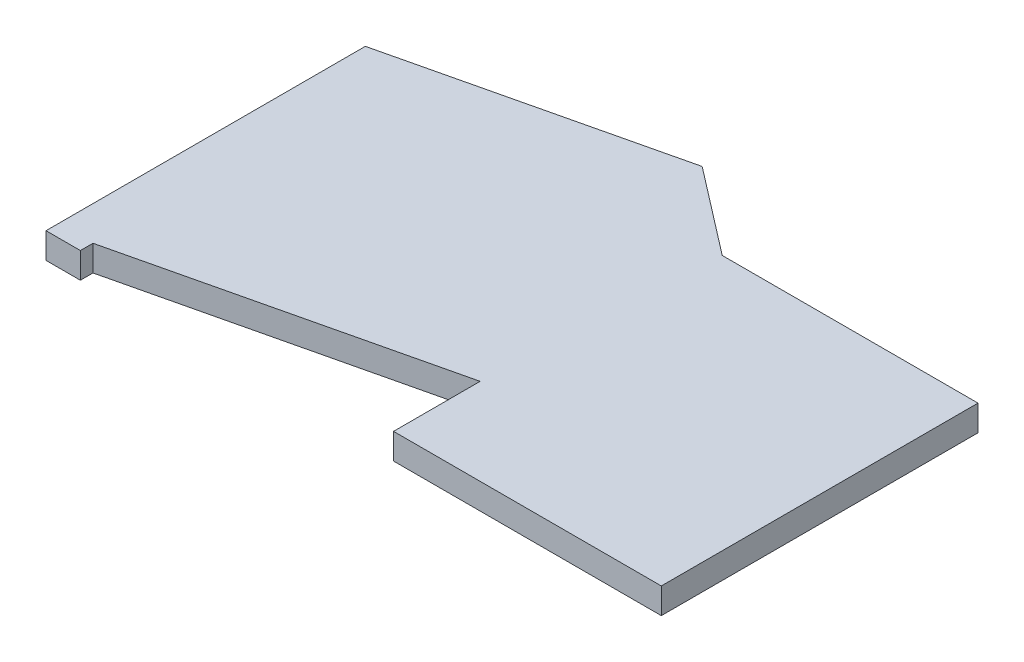
SolidWorks part; units mm, degrees
ref_plane "Front Plane" through (0, 0, 0) normal (0, 0, 1) x (1, 0, 0)
ref_plane "Top Plane" through (0, 0, 0) normal (0, 1, 0) x (1, 0, 0)
ref_plane "Right Plane" through (0, 0, 0) normal (1, 0, 0) x (0, 0, -1)
sketch "Sketch1" plane through (0, 70.2422, 0) normal (0, 1, 0) x (1, 0, 0)
  line L50 (64.166, -146.1853) -> (61.88, -146.1853)
  line L51 (64.166, -177.4273) -> (64.166, -146.1853)
  line L52 (37.75, -177.4273) -> (64.166, -177.4273)
  line L53 (64.166, -146.1853) -> (61.88, -146.1853)
  line L54 (64.166, -177.4273) -> (64.166, -146.1853)
  line L55 (37.75, -177.4273) -> (64.166, -177.4273)
  line L62 (38.865, -146.1326) -> (30.3426, -139.5733)
  line L63 (27.9883, -140.1297) -> (24.2804, -141.006)
  line L64 (30.3426, -139.5733) -> (27.9883, -140.1297)
  line L65 (38.865, -146.1326) -> (30.3426, -139.5733)
  line L66 (27.9883, -140.1297) -> (24.2804, -141.006)
  line L67 (30.3426, -139.5733) -> (27.9883, -140.1297)
  line L75 (9.449, -144.5112) -> (24.2804, -141.006)
  line L76 (61.88, -146.1853) -> (38.9335, -146.1853)
  line L77 (38.9335, -146.1853) -> (38.865, -146.1326)
  line L78 (6.856, -177.4273) -> (6.856, -176.1827)
  line L79 (3.4648, -177.4273) -> (6.856, -177.4273)
  line L80 (3.4648, -145.9255) -> (3.4648, -177.4273)
  line L81 (5.7411, -145.3875) -> (3.4648, -145.9255)
  line L82 (9.449, -144.5112) -> (5.7411, -145.3875)
  line L83 (3.4648, -177.4273) -> (6.856, -177.4273)
  line L84 (3.4648, -145.9255) -> (3.4648, -177.4273)
  line L85 (5.7411, -145.3875) -> (3.4648, -145.9255)
  line L86 (9.449, -144.5112) -> (5.7411, -145.3875)
  line L87 (6.856, -176.1827) -> (37.75, -168.8813)
  line L88 (37.75, -168.8813) -> (37.75, -177.4273)
  dimension "D1" = 0.254
  dimension "D2" = 0.254
  dimension "D3" = 0.254
extrude "Boss-Extrude1" add sketch "Sketch1" along normal blind 2.54
